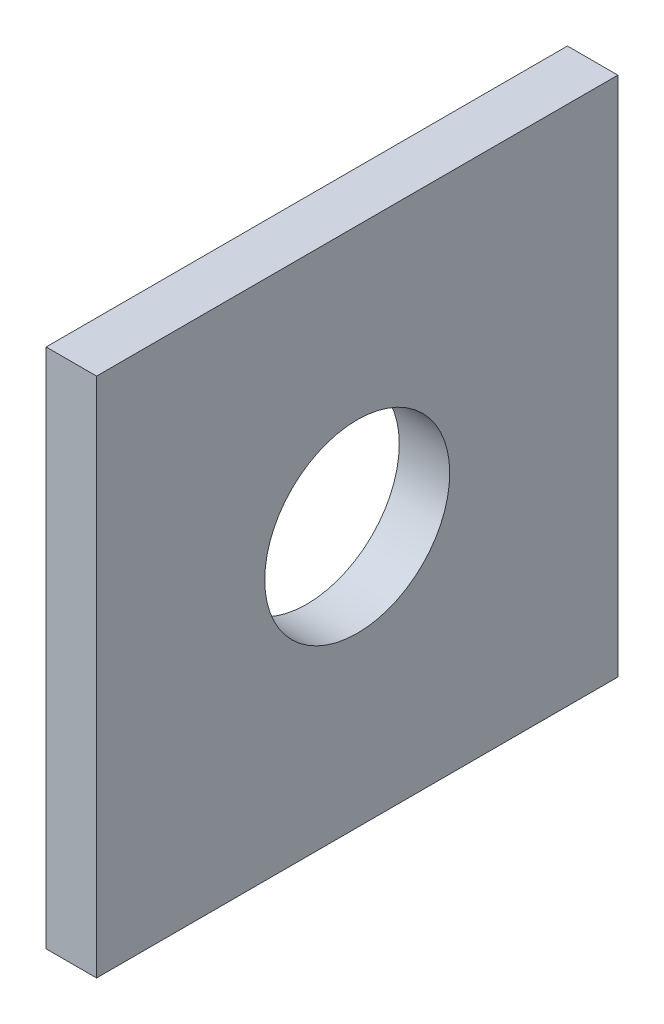
SolidWorks part; units mm, degrees
ref_plane "Plane1" through (0, 0, 0) normal (0, 0, 1) x (1, 0, 0)
ref_plane "Plane2" through (0, 0, 0) normal (0, 1, 0) x (1, 0, 0)
ref_plane "Plane3" through (0, 0, 0) normal (1, 0, 0) x (0, 0, -1)
sketch "Sketch1" plane through (0, 0, 0) normal (1, 0, 0) x (0, 0, -1)
  line L0 (-44.45, 0) -> (41.275, 0) construction
  line L1 (-31, -31) -> (31, -31)
  line L2 (-31, -31) -> (-31, 31)
  line L3 (-31, 31) -> (31, 31)
  line L4 (31, -31) -> (31, 31)
  line L5 (0, 41.275) -> (0, -38.1) construction
  circle A0 centre (0, 0) radius 11
  dimension "Inside_dia" = 22
  dimension "Outside_dia" = 62
extrude "Body" add sketch "Sketch1" against normal blind 6
